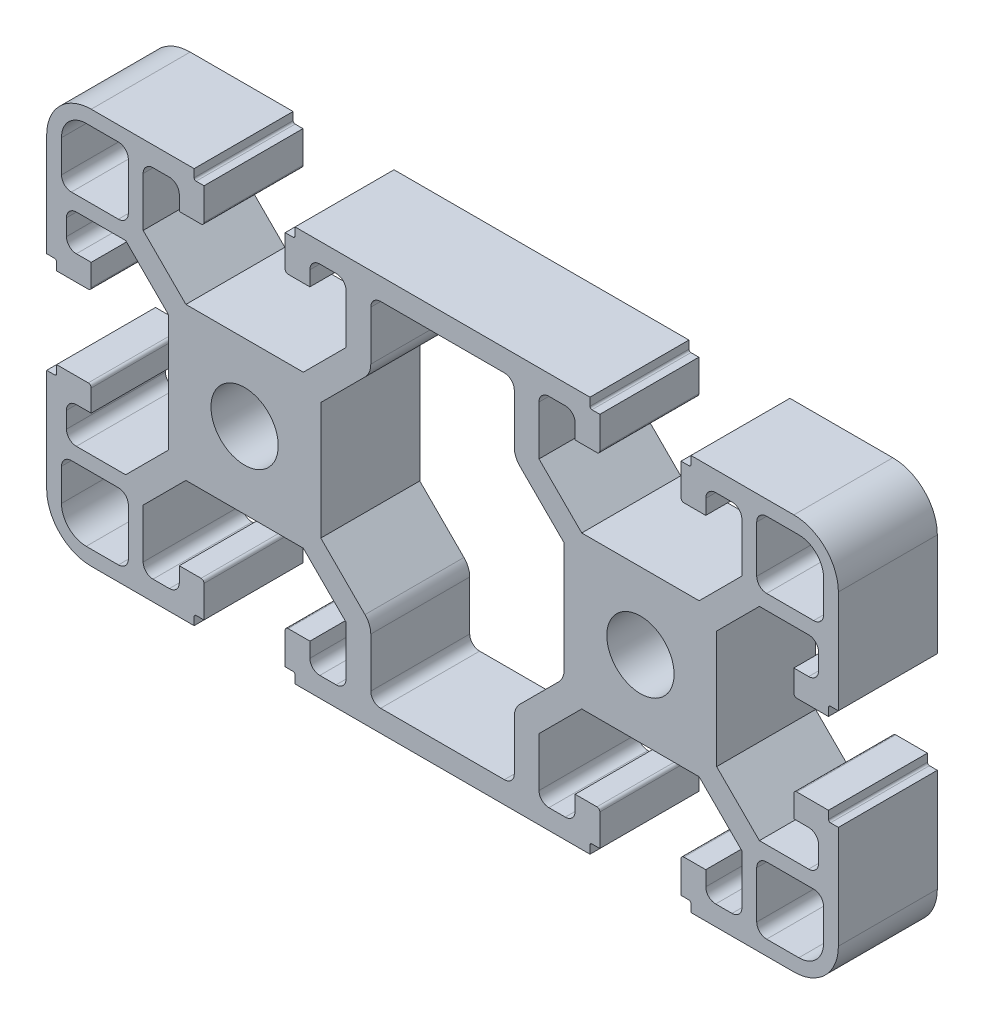
SolidWorks part; units mm, degrees
ref_plane "前视基准面" through (0, 0, 0) normal (0, 0, 1) x (1, 0, 0)
ref_plane "上视基准面" through (0, 0, 0) normal (0, 1, 0) x (1, 0, 0)
ref_plane "右视基准面" through (0, 0, 0) normal (1, 0, 0) x (0, 0, -1)
sketch "草图1" plane through (0, 0, 0) normal (0, 0, 1) x (1, 0, 0)
  line L0 (-26.6936, 19.8515) -> (-37.0936, 19.8515)
  line L1 (-41.5936, 15.3515) -> (-41.5936, 4.9515)
  line L2 (-28.1936, 15.3515) -> (-28.1936, 16.8515)
  line L3 (-29.1936, 17.8515) -> (-30.8436, 17.8515)
  line L4 (-31.8436, 16.8515) -> (-31.8436, 11.8693)
  line L5 (-25.6936, 18.8515) -> (-26.4936, 18.8515)
  line L6 (-26.6936, 19.0515) -> (-26.6936, 19.8515)
  line L7 (-41.5936, 4.9515) -> (-40.7936, 4.9515)
  line L8 (-40.5936, 4.7515) -> (-40.5936, 3.9515)
  line L9 (-37.0936, 6.4515) -> (-37.0936, 4.2515)
  line L10 (-37.3936, 3.9515) -> (-40.5936, 3.9515)
  line L11 (-25.6936, 18.8515) -> (-25.6936, 15.6515)
  line L12 (-25.9936, 15.3515) -> (-28.1936, 15.3515)
  line L13 (-27.5259, 7.5515) -> (-15.6614, 7.5515)
  line L14 (-40.0976, 15.8555) -> (-40.0976, 12.6015)
  line L15 (-39.0976, 11.6015) -> (-34.3436, 11.6015)
  line L16 (-33.3436, 12.6015) -> (-33.3436, 17.3555)
  line L17 (-34.3436, 18.3555) -> (-37.5976, 18.3555)
  line L18 (-27.5259, -7.8485) -> (-15.6614, -7.8485)
  line L19 (-29.2936, 5.7837) -> (-29.2936, -6.0807)
  line L21 (-13.8936, -6.0807) -> (-13.8936, 5.7837)
  line L23 (-33.6114, 10.1015) -> (-29.2936, 5.7837)
  line L24 (-31.8436, 11.8693) -> (-27.5259, 7.5515)
  line L25 (-37.0936, 6.4515) -> (-38.5936, 6.4515)
  line L26 (-39.5936, 7.4515) -> (-39.5936, 9.1015)
  line L27 (-38.5936, 10.1015) -> (-33.6114, 10.1015)
  line L28 (-16.4936, 19.8515) -> (-6.0936, 19.8515)
  line L29 (-14.9936, 15.3515) -> (-14.9936, 16.8515)
  line L30 (-13.9936, 17.8515) -> (-12.3436, 17.8515)
  line L31 (-11.3436, 16.8515) -> (-11.3436, 11.8693)
  line L32 (-8.8436, 16.6515) -> (-8.8436, 11.6622)
  line L33 (-17.4936, 18.8515) -> (-16.6936, 18.8515)
  line L34 (-16.4936, 19.0515) -> (-16.4936, 19.8515)
  line L35 (-17.4936, 18.8515) -> (-17.4936, 15.6515)
  line L36 (-17.1936, 15.3515) -> (-14.9936, 15.3515)
  line L37 (-9.4294, 10.248) -> (-13.8936, 5.7837)
  line L38 (-11.3436, 11.8693) -> (-15.6614, 7.5515)
  line L39 (-26.6936, -20.1485) -> (-37.0936, -20.1485)
  line L40 (-41.5936, -15.6485) -> (-41.5936, -5.2485)
  line L41 (-28.1936, -15.6485) -> (-28.1936, -17.1485)
  line L42 (-29.1936, -18.1485) -> (-30.8436, -18.1485)
  line L43 (-31.8436, -17.1485) -> (-31.8436, -12.1663)
  line L44 (-25.6936, -19.1485) -> (-26.4936, -19.1485)
  line L45 (-26.6936, -19.3485) -> (-26.6936, -20.1485)
  line L46 (-41.5936, -5.2485) -> (-40.7936, -5.2485)
  line L47 (-40.5936, -5.0485) -> (-40.5936, -4.2485)
  line L48 (-37.0936, -6.7485) -> (-37.0936, -4.5485)
  line L49 (-37.3936, -4.2485) -> (-40.5936, -4.2485)
  line L50 (-25.6936, -19.1485) -> (-25.6936, -15.9485)
  line L51 (-25.9936, -15.6485) -> (-28.1936, -15.6485)
  line L52 (-40.0976, -16.1525) -> (-40.0976, -12.8985)
  line L53 (-39.0976, -11.8985) -> (-34.3436, -11.8985)
  line L54 (-33.3436, -12.8985) -> (-33.3436, -17.6525)
  line L55 (-34.3436, -18.6525) -> (-37.5976, -18.6525)
  line L56 (-33.6114, -10.3985) -> (-29.2936, -6.0807)
  line L57 (-31.8436, -12.1663) -> (-27.5259, -7.8485)
  line L58 (-37.0936, -6.7485) -> (-38.5936, -6.7485)
  line L59 (-39.5936, -7.7485) -> (-39.5936, -9.3985)
  line L60 (-38.5936, -10.3985) -> (-33.6114, -10.3985)
  line L61 (-16.4936, -20.1485) -> (-6.0936, -20.1485)
  line L62 (-14.9936, -15.6485) -> (-14.9936, -17.1485)
  line L63 (-13.9936, -18.1485) -> (-12.3436, -18.1485)
  line L64 (-11.3436, -17.1485) -> (-11.3436, -12.1663)
  line L65 (-17.4936, -19.1485) -> (-16.6936, -19.1485)
  line L66 (-16.4936, -19.3485) -> (-16.4936, -20.1485)
  line L67 (-17.4936, -19.1485) -> (-17.4936, -15.9485)
  line L68 (-17.1936, -15.6485) -> (-14.9936, -15.6485)
  line L69 (-9.4294, -10.5449) -> (-13.8936, -6.0807)
  line L70 (-11.3436, -12.1663) -> (-15.6614, -7.8485)
  line L71 (13.3064, 19.8515) -> (2.9064, 19.8515)
  line L72 (11.8064, 15.3515) -> (11.8064, 16.8515)
  line L73 (10.8064, 17.8515) -> (9.1564, 17.8515)
  line L74 (8.1564, 16.8515) -> (8.1564, 11.8693)
  line L75 (5.6564, 16.6515) -> (5.6564, 11.6622)
  line L76 (14.3064, 18.8515) -> (13.5064, 18.8515)
  line L77 (13.3064, 19.0515) -> (13.3064, 19.8515)
  line L78 (14.3064, 18.8515) -> (14.3064, 15.6515)
  line L79 (14.0064, 15.3515) -> (11.8064, 15.3515)
  line L80 (12.4741, 7.5515) -> (24.3386, 7.5515)
  line L81 (12.4741, -7.8485) -> (24.3386, -7.8485)
  line L82 (10.7064, 5.7837) -> (10.7064, -5.2523)
  line L83 (10.1206, -6.6665) -> (6.2422, -10.5449)
  line L85 (26.1064, -6.0807) -> (26.1064, 5.7837)
  line L87 (6.2422, 10.248) -> (10.7064, 5.7837)
  line L88 (8.1564, 11.8693) -> (12.4741, 7.5515)
  line L89 (23.5064, 19.8515) -> (33.9064, 19.8515)
  line L90 (38.4064, 15.3515) -> (38.4064, 4.9515)
  line L91 (25.0064, 15.3515) -> (25.0064, 16.8515)
  line L92 (26.0064, 17.8515) -> (27.6564, 17.8515)
  line L93 (28.6564, 16.8515) -> (28.6564, 11.8693)
  line L94 (22.5064, 18.8515) -> (23.3064, 18.8515)
  line L95 (23.5064, 19.0515) -> (23.5064, 19.8515)
  line L96 (38.4064, 4.9515) -> (37.6064, 4.9515)
  line L97 (37.4064, 4.7515) -> (37.4064, 3.9515)
  line L98 (33.9064, 6.4515) -> (33.9064, 4.2515)
  line L99 (34.2064, 3.9515) -> (37.4064, 3.9515)
  line L100 (22.5064, 18.8515) -> (22.5064, 15.6515)
  line L101 (22.8064, 15.3515) -> (25.0064, 15.3515)
  line L102 (36.9104, 15.8555) -> (36.9104, 12.6015)
  line L103 (35.9104, 11.6015) -> (31.1564, 11.6015)
  line L104 (30.1564, 12.6015) -> (30.1564, 17.3555)
  line L105 (31.1564, 18.3555) -> (34.4104, 18.3555)
  line L106 (30.4241, 10.1015) -> (26.1064, 5.7837)
  line L107 (28.6564, 11.8693) -> (24.3386, 7.5515)
  line L108 (33.9064, 6.4515) -> (35.4064, 6.4515)
  line L109 (36.4064, 7.4515) -> (36.4064, 9.1015)
  line L110 (35.4064, 10.1015) -> (30.4241, 10.1015)
  line L111 (13.3064, -20.1485) -> (2.9064, -20.1485)
  line L112 (11.8064, -15.6485) -> (11.8064, -17.1485)
  line L113 (10.8064, -18.1485) -> (9.1564, -18.1485)
  line L114 (8.1564, -17.1485) -> (8.1564, -12.1663)
  line L115 (14.3064, -19.1485) -> (13.5064, -19.1485)
  line L116 (13.3064, -19.3485) -> (13.3064, -20.1485)
  line L117 (14.3064, -19.1485) -> (14.3064, -15.9485)
  line L118 (14.0064, -15.6485) -> (11.8064, -15.6485)
  line L119 (8.1564, -12.1663) -> (12.4741, -7.8485)
  line L120 (23.5064, -20.1485) -> (33.9064, -20.1485)
  line L121 (38.4064, -15.6485) -> (38.4064, -5.2485)
  line L122 (25.0064, -15.6485) -> (25.0064, -17.1485)
  line L123 (26.0064, -18.1485) -> (27.6564, -18.1485)
  line L124 (28.6564, -17.1485) -> (28.6564, -12.1663)
  line L125 (22.5064, -19.1485) -> (23.3064, -19.1485)
  line L126 (23.5064, -19.3485) -> (23.5064, -20.1485)
  line L127 (38.4064, -5.2485) -> (37.6064, -5.2485)
  line L128 (37.4064, -5.0485) -> (37.4064, -4.2485)
  line L129 (33.9064, -6.7485) -> (33.9064, -4.5485)
  line L130 (34.2064, -4.2485) -> (37.4064, -4.2485)
  line L131 (22.5064, -19.1485) -> (22.5064, -15.9485)
  line L132 (22.8064, -15.6485) -> (25.0064, -15.6485)
  line L133 (36.9104, -16.1525) -> (36.9104, -12.8985)
  line L134 (35.9104, -11.8985) -> (31.1564, -11.8985)
  line L135 (30.1564, -12.8985) -> (30.1564, -17.6525)
  line L136 (31.1564, -18.6525) -> (34.4104, -18.6525)
  line L137 (30.4241, -10.3985) -> (26.1064, -6.0807)
  line L138 (28.6564, -12.1663) -> (24.3386, -7.8485)
  line L139 (33.9064, -6.7485) -> (35.4064, -6.7485)
  line L140 (36.4064, -7.7485) -> (36.4064, -9.3985)
  line L141 (35.4064, -10.3985) -> (30.4241, -10.3985)
  line L142 (-6.0936, -20.1485) -> (2.9064, -20.1485)
  line L143 (-6.0936, 19.8515) -> (2.9064, 19.8515)
  line L144 (4.6564, 17.6515) -> (-7.8436, 17.6515)
  line L145 (-8.8436, -16.9485) -> (-8.8436, -11.9591)
  line L146 (5.6564, -16.9485) -> (5.6564, -11.9591)
  line L147 (4.6564, -17.9485) -> (-7.8436, -17.9485)
  arc A0 (-37.0936, 19.8515) -> (-41.5936, 15.3515) centre (-37.0936, 15.3515) ccw
  arc A1 (-28.1936, 16.8515) -> (-29.1936, 17.8515) centre (-29.1936, 16.8515) ccw
  arc A2 (-30.8436, 17.8515) -> (-31.8436, 16.8515) centre (-30.8436, 16.8515) ccw
  arc A3 (-26.6936, 19.0515) -> (-26.4936, 18.8515) centre (-26.4936, 19.0515) ccw
  arc A4 (-40.5936, 4.7515) -> (-40.7936, 4.9515) centre (-40.7936, 4.7515) ccw
  arc A5 (-37.3936, 3.9515) -> (-37.0936, 4.2515) centre (-37.3936, 4.2515) ccw
  arc A6 (-25.9936, 15.3515) -> (-25.6936, 15.6515) centre (-25.9936, 15.6515) ccw
  circle A7 centre (-21.5936, -0.1485) radius 3.4
  arc A8 (-40.0976, 12.6015) -> (-39.0976, 11.6015) centre (-39.0976, 12.6015) ccw
  arc A9 (-33.3436, 17.3555) -> (-34.3436, 18.3555) centre (-34.3436, 17.3555) ccw
  arc A10 (-34.3436, 11.6015) -> (-33.3436, 12.6015) centre (-34.3436, 12.6015) ccw
  arc A11 (-37.5976, 18.3555) -> (-40.0976, 15.8555) centre (-37.5976, 15.8555) ccw
  arc A12 (-39.5936, 7.4515) -> (-38.5936, 6.4515) centre (-38.5936, 7.4515) ccw
  arc A13 (-38.5936, 10.1015) -> (-39.5936, 9.1015) centre (-38.5936, 9.1015) ccw
  arc A14 (-13.9936, 17.8515) -> (-14.9936, 16.8515) centre (-13.9936, 16.8515) ccw
  arc A15 (-11.3436, 16.8515) -> (-12.3436, 17.8515) centre (-12.3436, 16.8515) ccw
  arc A16 (-16.6936, 18.8515) -> (-16.4936, 19.0515) centre (-16.6936, 19.0515) ccw
  arc A17 (-17.4936, 15.6515) -> (-17.1936, 15.3515) centre (-17.1936, 15.6515) ccw
  arc A18 (-9.4294, 10.248) -> (-8.8436, 11.6622) centre (-10.8436, 11.6622) ccw
  arc A19 (-41.5936, -15.6485) -> (-37.0936, -20.1485) centre (-37.0936, -15.6485) ccw
  arc A20 (-29.1936, -18.1485) -> (-28.1936, -17.1485) centre (-29.1936, -17.1485) ccw
  arc A21 (-31.8436, -17.1485) -> (-30.8436, -18.1485) centre (-30.8436, -17.1485) ccw
  arc A22 (-26.4936, -19.1485) -> (-26.6936, -19.3485) centre (-26.4936, -19.3485) ccw
  arc A23 (-40.7936, -5.2485) -> (-40.5936, -5.0485) centre (-40.7936, -5.0485) ccw
  arc A24 (-37.0936, -4.5485) -> (-37.3936, -4.2485) centre (-37.3936, -4.5485) ccw
  arc A25 (-25.6936, -15.9485) -> (-25.9936, -15.6485) centre (-25.9936, -15.9485) ccw
  arc A26 (-39.0976, -11.8985) -> (-40.0976, -12.8985) centre (-39.0976, -12.8985) ccw
  arc A27 (-34.3436, -18.6525) -> (-33.3436, -17.6525) centre (-34.3436, -17.6525) ccw
  arc A28 (-33.3436, -12.8985) -> (-34.3436, -11.8985) centre (-34.3436, -12.8985) ccw
  arc A29 (-40.0976, -16.1525) -> (-37.5976, -18.6525) centre (-37.5976, -16.1525) ccw
  arc A30 (-38.5936, -6.7485) -> (-39.5936, -7.7485) centre (-38.5936, -7.7485) ccw
  arc A31 (-39.5936, -9.3985) -> (-38.5936, -10.3985) centre (-38.5936, -9.3985) ccw
  arc A32 (-14.9936, -17.1485) -> (-13.9936, -18.1485) centre (-13.9936, -17.1485) ccw
  arc A33 (-12.3436, -18.1485) -> (-11.3436, -17.1485) centre (-12.3436, -17.1485) ccw
  arc A34 (-16.4936, -19.3485) -> (-16.6936, -19.1485) centre (-16.6936, -19.3485) ccw
  arc A35 (-17.1936, -15.6485) -> (-17.4936, -15.9485) centre (-17.1936, -15.9485) ccw
  arc A36 (-8.8436, -11.9591) -> (-9.4294, -10.5449) centre (-10.8436, -11.9591) ccw
  arc A37 (11.8064, 16.8515) -> (10.8064, 17.8515) centre (10.8064, 16.8515) ccw
  arc A38 (5.6564, 16.6515) -> (4.6564, 17.6515) centre (4.6564, 16.6515) ccw
  arc A39 (9.1564, 17.8515) -> (8.1564, 16.8515) centre (9.1564, 16.8515) ccw
  arc A40 (13.3064, 19.0515) -> (13.5064, 18.8515) centre (13.5064, 19.0515) ccw
  arc A41 (14.0064, 15.3515) -> (14.3064, 15.6515) centre (14.0064, 15.6515) ccw
  circle A42 centre (18.4064, -0.1485) radius 3.4
  arc A43 (10.1206, -6.6665) -> (10.7064, -5.2523) centre (8.7064, -5.2523) ccw
  arc A44 (5.6564, 11.6622) -> (6.2422, 10.248) centre (7.6564, 11.6622) ccw
  arc A45 (38.4064, 15.3515) -> (33.9064, 19.8515) centre (33.9064, 15.3515) ccw
  arc A46 (26.0064, 17.8515) -> (25.0064, 16.8515) centre (26.0064, 16.8515) ccw
  arc A47 (28.6564, 16.8515) -> (27.6564, 17.8515) centre (27.6564, 16.8515) ccw
  arc A48 (23.3064, 18.8515) -> (23.5064, 19.0515) centre (23.3064, 19.0515) ccw
  arc A49 (37.6064, 4.9515) -> (37.4064, 4.7515) centre (37.6064, 4.7515) ccw
  arc A50 (33.9064, 4.2515) -> (34.2064, 3.9515) centre (34.2064, 4.2515) ccw
  arc A51 (22.5064, 15.6515) -> (22.8064, 15.3515) centre (22.8064, 15.6515) ccw
  arc A52 (35.9104, 11.6015) -> (36.9104, 12.6015) centre (35.9104, 12.6015) ccw
  arc A53 (31.1564, 18.3555) -> (30.1564, 17.3555) centre (31.1564, 17.3555) ccw
  arc A54 (30.1564, 12.6015) -> (31.1564, 11.6015) centre (31.1564, 12.6015) ccw
  arc A55 (36.9104, 15.8555) -> (34.4104, 18.3555) centre (34.4104, 15.8555) ccw
  arc A56 (35.4064, 6.4515) -> (36.4064, 7.4515) centre (35.4064, 7.4515) ccw
  arc A57 (36.4064, 9.1015) -> (35.4064, 10.1015) centre (35.4064, 9.1015) ccw
  arc A58 (10.8064, -18.1485) -> (11.8064, -17.1485) centre (10.8064, -17.1485) ccw
  arc A59 (8.1564, -17.1485) -> (9.1564, -18.1485) centre (9.1564, -17.1485) ccw
  arc A60 (13.5064, -19.1485) -> (13.3064, -19.3485) centre (13.5064, -19.3485) ccw
  arc A61 (14.3064, -15.9485) -> (14.0064, -15.6485) centre (14.0064, -15.9485) ccw
  arc A62 (6.2422, -10.5449) -> (5.6564, -11.9591) centre (7.6564, -11.9591) ccw
  arc A63 (33.9064, -20.1485) -> (38.4064, -15.6485) centre (33.9064, -15.6485) ccw
  arc A64 (25.0064, -17.1485) -> (26.0064, -18.1485) centre (26.0064, -17.1485) ccw
  arc A65 (27.6564, -18.1485) -> (28.6564, -17.1485) centre (27.6564, -17.1485) ccw
  arc A66 (23.5064, -19.3485) -> (23.3064, -19.1485) centre (23.3064, -19.3485) ccw
  arc A67 (37.4064, -5.0485) -> (37.6064, -5.2485) centre (37.6064, -5.0485) ccw
  arc A68 (34.2064, -4.2485) -> (33.9064, -4.5485) centre (34.2064, -4.5485) ccw
  arc A69 (22.8064, -15.6485) -> (22.5064, -15.9485) centre (22.8064, -15.9485) ccw
  arc A70 (36.9104, -12.8985) -> (35.9104, -11.8985) centre (35.9104, -12.8985) ccw
  arc A71 (30.1564, -17.6525) -> (31.1564, -18.6525) centre (31.1564, -17.6525) ccw
  arc A72 (31.1564, -11.8985) -> (30.1564, -12.8985) centre (31.1564, -12.8985) ccw
  arc A73 (34.4104, -18.6525) -> (36.9104, -16.1525) centre (34.4104, -16.1525) ccw
  arc A74 (36.4064, -7.7485) -> (35.4064, -6.7485) centre (35.4064, -7.7485) ccw
  arc A75 (35.4064, -10.3985) -> (36.4064, -9.3985) centre (35.4064, -9.3985) ccw
  arc A76 (-7.8436, 17.6515) -> (-8.8436, 16.6515) centre (-7.8436, 16.6515) ccw
  arc A77 (-8.8436, -16.9485) -> (-7.8436, -17.9485) centre (-7.8436, -16.9485) ccw
  arc A78 (4.6564, -17.9485) -> (5.6564, -16.9485) centre (4.6564, -16.9485) ccw
extrude "凸台-拉伸1" add sketch "草图1" along normal blind 10
